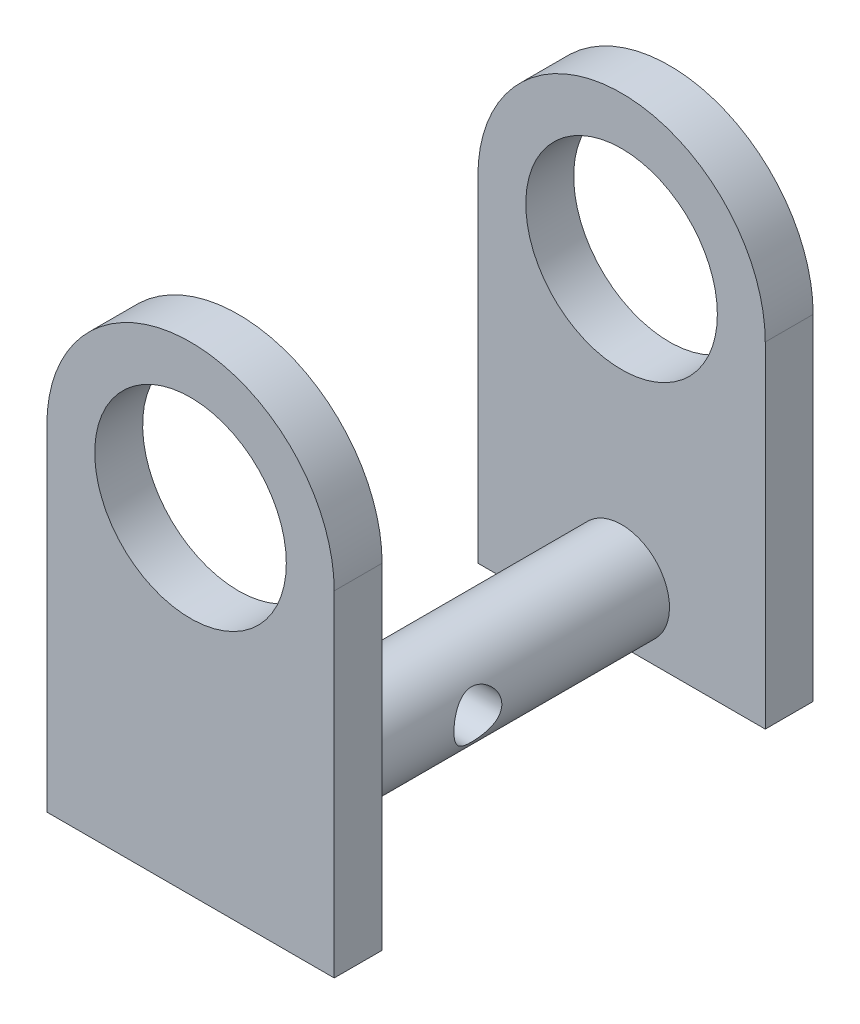
SolidWorks part; units mm, degrees
material "AISI 304"
ref_plane "Front Plane" through (0, 0, 0) normal (0, 0, 1) x (1, 0, 0)
ref_plane "Top Plane" through (0, 0, 0) normal (0, 1, 0) x (1, 0, 0)
ref_plane "Right Plane" through (0, 0, 0) normal (1, 0, 0) x (0, 0, -1)
sketch "Sketch2" plane through (0, 0, 0) normal (0, 0, 1) x (1, 0, 0)
  line L0 (-15, 0) -> (-15, -35)
  line L1 (15, 0) -> (15, -35)
  line L2 (15, -35) -> (-15, -35)
  arc A0 (15, 0) -> (-15, 0) centre (0, 0) ccw
  circle A1 centre (0, 0) radius 10
  dimension "D1" = 20
  dimension "D2" = 30
  dimension "D3" = 35
extrude "Boss-Extrude1" add sketch "Sketch2" against normal blind 50 contours L1 A0 L0 L2 A1
sketch "Sketch3" plane through (15, 0, 0) normal (1, 0, 0) x (0, 0, -1)
  line L0 (50, 15) -> (0, 15) construction
  line L1 (5, 15) -> (45, 15)
  line L2 (5, 15) -> (5, -35)
  line L3 (5, -35) -> (45, -35)
  line L4 (45, 15) -> (45, -35)
  line L5 (0, 15) -> (0, 0) construction
  line L6 (50, 0) -> (50, 15) construction
  line L7 (50, -35) -> (0, -35) construction
  dimension "D1" = 5
  dimension "D2" = 5
  dimension "D3" = 0
extrude "Cut-Extrude1" cut sketch "Sketch3" against normal blind 55
sketch "Sketch4" plane through (0, 0, -50) normal (0, 0, -1) x (-1, 0, 0)
  line L0 (-15, -35) -> (15, -35) construction
  circle A0 centre (0, -29) radius 5
  dimension "D1" = 10
  dimension "D2" = 6
extrude "Boss-Extrude2" add sketch "Sketch4" against normal blind 48
sketch "Sketch5" plane through (0, 0, 0) normal (1, 0, 0) x (0, 0, -1)
  line L0 (45, -24) -> (5, -24) construction
  circle A0 centre (25, -29) radius 2.5
  dimension "D1" = 5
  dimension "D2" = 5
extrude "Cut-Extrude2" cut sketch "Sketch5" against normal mid plane 20
